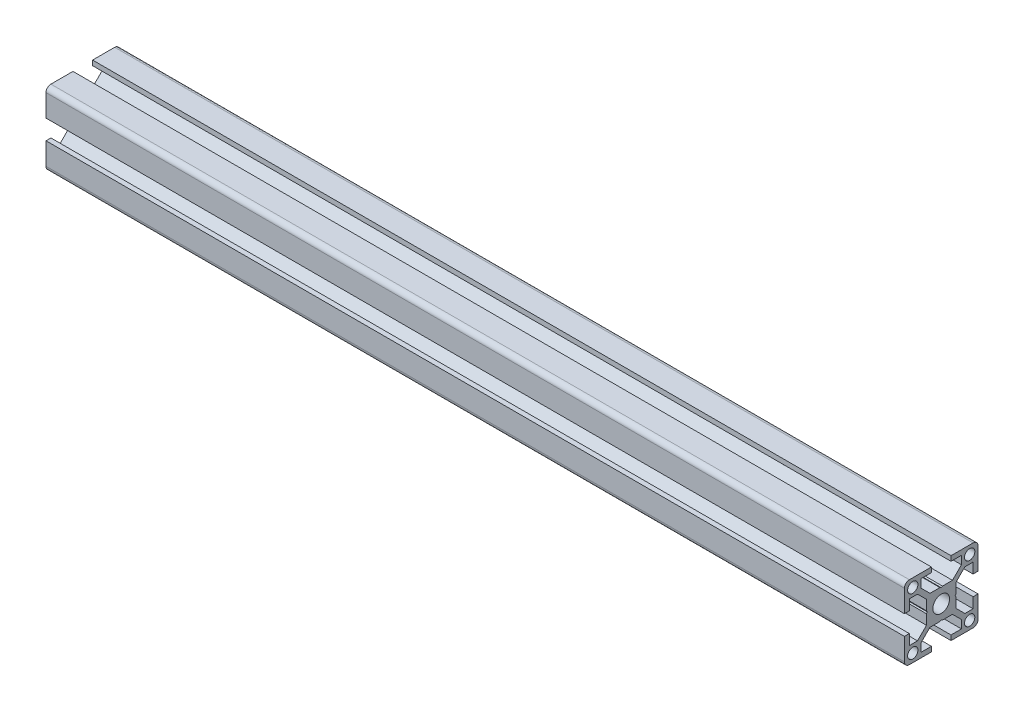
SolidWorks part; units mm, degrees
ref_plane "Front Plane" through (0, 0, 0) normal (0, 0, 1) x (1, 0, 0)
ref_plane "Top Plane" through (0, 0, 0) normal (0, 1, 0) x (1, 0, 0)
ref_plane "Right Plane" through (0, 0, 0) normal (1, 0, 0) x (0, 0, -1)
ref_plane "Plane1" through (0, 0, 0) normal (-1, 0, 0) x (0, -1, 0)
sketch "Sketch1" plane through (0, 0, 0) normal (-1, 0, 0) x (0, -1, 0)
  line L0 (13, -4) -> (13, -8.25)
  line L1 (13, -8.25) -> (9.6642, -8.25)
  line L2 (9.6642, -8.25) -> (6, -4.5858)
  line L3 (6, -4.5858) -> (6, -0.5196)
  line L4 (6, -0.5196) -> (5.7, 0)
  line L5 (5.7, 0) -> (6, 0.5196)
  line L6 (6, 0.5196) -> (6, 4.5858)
  line L7 (6, 4.5858) -> (9.6642, 8.25)
  line L8 (9.6642, 8.25) -> (13, 8.25)
  line L9 (13, 8.25) -> (13, 4)
  line L10 (13, 4) -> (15, 4)
  line L11 (15, 4) -> (15, 13)
  line L12 (13, 15) -> (4, 15)
  line L13 (4, 15) -> (4, 13)
  line L14 (4, 13) -> (8.25, 13)
  line L15 (8.25, 13) -> (8.25, 9.6642)
  line L16 (8.25, 9.6642) -> (4.5858, 6)
  line L17 (4.5858, 6) -> (0.5196, 6)
  line L18 (0.5196, 6) -> (0, 5.7)
  line L19 (0, 5.7) -> (-0.5196, 6)
  line L20 (-0.5196, 6) -> (-4.5858, 6)
  line L21 (-4.5858, 6) -> (-8.25, 9.6642)
  line L22 (-8.25, 9.6642) -> (-8.25, 13)
  line L23 (-8.25, 13) -> (-4, 13)
  line L24 (-4, 13) -> (-4, 15)
  line L25 (-4, 15) -> (-13, 15)
  line L26 (-15, 13) -> (-15, 4)
  line L27 (-15, 4) -> (-13, 4)
  line L28 (-13, 4) -> (-13, 8.25)
  line L29 (-13, 8.25) -> (-9.6642, 8.25)
  line L30 (-9.6642, 8.25) -> (-6, 4.5858)
  line L31 (-6, 4.5858) -> (-6, 0.5196)
  line L32 (-6, 0.5196) -> (-5.7, 0)
  line L33 (-5.7, 0) -> (-6, -0.5196)
  line L34 (-6, -0.5196) -> (-6, -4.5858)
  line L35 (-6, -4.5858) -> (-9.6642, -8.25)
  line L36 (-9.6642, -8.25) -> (-13, -8.25)
  line L37 (-13, -8.25) -> (-13, -4)
  line L38 (-13, -4) -> (-15, -4)
  line L39 (-15, -4) -> (-15, -13)
  line L40 (-13, -15) -> (-4, -15)
  line L41 (-4, -15) -> (-4, -13)
  line L42 (-4, -13) -> (-8.25, -13)
  line L43 (-8.25, -13) -> (-8.25, -9.6642)
  line L44 (-8.25, -9.6642) -> (-4.5858, -6)
  line L45 (-4.5858, -6) -> (-0.5196, -6)
  line L46 (-0.5196, -6) -> (0, -5.7)
  line L47 (0, -5.7) -> (0.5196, -6)
  line L48 (0.5196, -6) -> (4.5858, -6)
  line L49 (4.5858, -6) -> (8.25, -9.6642)
  line L50 (8.25, -9.6642) -> (8.25, -13)
  line L51 (8.25, -13) -> (4, -13)
  line L52 (4, -13) -> (4, -15)
  line L53 (4, -15) -> (13, -15)
  line L54 (15, -13) -> (15, -4)
  line L55 (15, -4) -> (13, -4)
  arc A0 (15, 13) -> (13, 15) centre (13, 13) ccw
  arc A1 (-13, 15) -> (-15, 13) centre (-13, 13) ccw
  arc A2 (-15, -13) -> (-13, -15) centre (-13, -13) ccw
  arc A3 (13, -15) -> (15, -13) centre (13, -13) ccw
  circle A4 centre (0, 0) radius 3.4
  circle A5 centre (11.6, -11.6) radius 2.1
  circle A6 centre (11.6, 11.6) radius 2.1
  circle A7 centre (-11.6, 11.6) radius 2.1
  circle A8 centre (-11.6, -11.6) radius 2.1
extrude "Boss-Extrude1" add sketch "Sketch1" against normal blind 350
